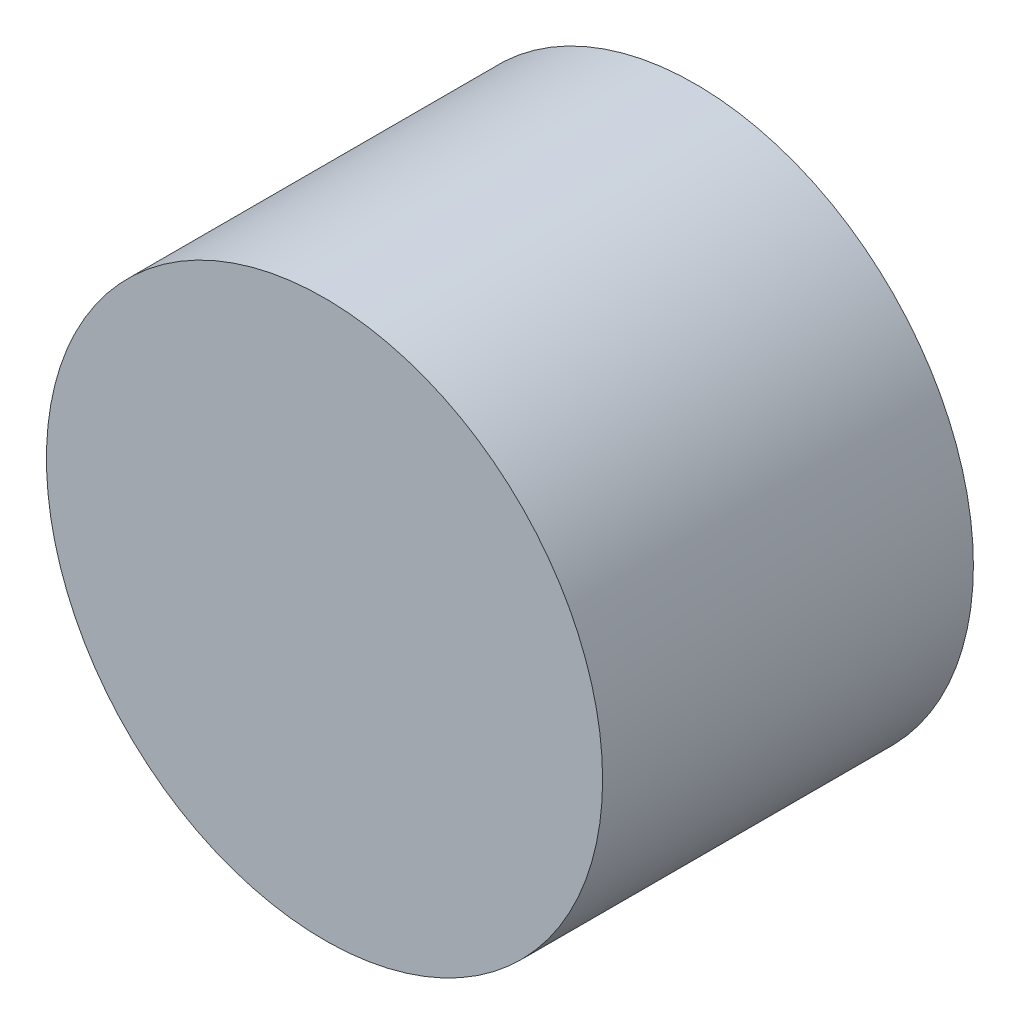
SolidWorks part; units mm, degrees
ref_plane "Alzado" through (0, 0, 0) normal (0, 0, 1) x (1, 0, 0)
ref_plane "Planta" through (0, 0, 0) normal (0, 1, 0) x (1, 0, 0)
ref_plane "Vista lateral" through (0, 0, 0) normal (1, 0, 0) x (0, 0, -1)
sketch "Croquis1" plane through (0, 0, 0) normal (0, 0, 1) x (1, 0, 0)
  circle A0 centre (0, 0) radius 12
  dimension "D1" = 24
extrude "Saliente-Extruir1" add sketch "Croquis1" along normal blind 16
ref_plane "Plano1" through (-12, 0, 0) normal (-1, 0, 0) x (0, 0, 1)
sketch "Croquis3" plane through (-12, 0, 0) normal (-1, 0, 0) x (0, 0, 1)
  line L0 (16, -12) -> (16, 12) construction
  line L1 (1, -6) -> (7, -6)
  line L2 (1, -6) -> (1, 6)
  line L3 (1, 6) -> (7, 6)
  line L4 (7, -6) -> (7, 6)
  line L5 (1, -6) -> (7, 6) construction
  line L6 (1, 6) -> (7, -6) construction
  point P0 (4, 0)
  point P5 (8.3569, 0)
  dimension "D1" = 6
  dimension "D2" = 12
  dimension "D3" = 9
extrude "Cortar-Extruir1" cut sketch "Croquis3" against normal blind 9 and the other way blind 1
